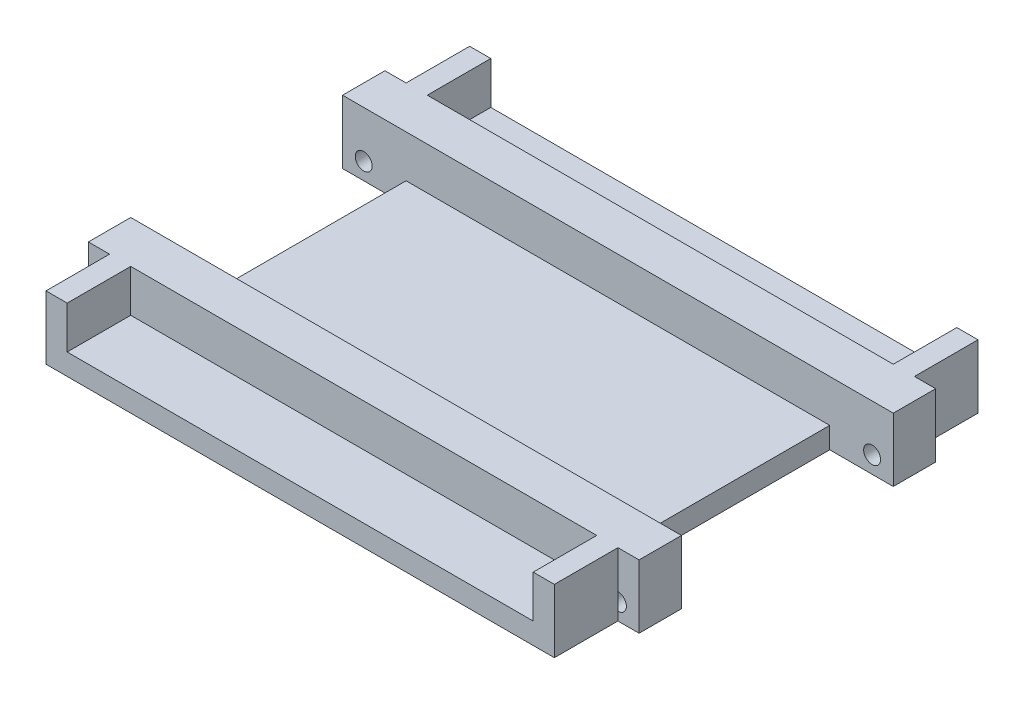
SolidWorks part; units mm, degrees
ref_plane "Front Plane" through (0, 0, 0) normal (0, 0, 1) x (1, 0, 0)
ref_plane "Top Plane" through (0, 0, 0) normal (0, 1, 0) x (1, 0, 0)
ref_plane "Right Plane" through (0, 0, 0) normal (1, 0, 0) x (0, 0, -1)
sketch "Sketch1" plane through (0, 0, 0) normal (0, 1, 0) x (1, 0, 0)
  line L1 (-50, 25) -> (50, 25)
  line L2 (-50, 25) -> (-50, -25)
  line L3 (-50, -25) -> (50, -25)
  line L4 (50, 25) -> (50, -25)
  line L5 (-50, 25) -> (50, -25) construction
  line L6 (-50, -25) -> (50, 25) construction
  point P0 (0, 0)
  dimension "D1" = 100
  dimension "D2" = 50
extrude "Boss-Extrude1" add sketch "Sketch1" along normal blind 5
sketch "Sketch2" plane through (0, 0, 25) normal (0, 0, 1) x (1, 0, 0)
  line L1 (-65, 15) -> (65, 15)
  line L2 (-65, 15) -> (-65, 0)
  line L3 (-65, 0) -> (65, 0)
  line L4 (65, 15) -> (65, 0)
  line L5 (-65, 15) -> (65, 0) construction
  line L6 (-65, 0) -> (65, 15) construction
  line L7 (-50, 5) -> (50, 5) construction
  point P0 (0, 7.5)
  dimension "D1" = 130
  dimension "D2" = 15
  dimension "D3" = 10
extrude "Boss-Extrude2" add sketch "Sketch2" along normal blind 10
sketch "Sketch3" plane through (0, 0, -25) normal (0, 0, -1) x (-1, 0, 0)
  line L1 (-65, 15) -> (65, 15)
  line L2 (-65, 15) -> (-65, 0)
  line L3 (-65, 0) -> (65, 0)
  line L4 (65, 15) -> (65, 0)
extrude "Boss-Extrude3" add sketch "Sketch3" along normal blind 10
sketch "Sketch4" plane through (0, 0, 35) normal (0, 0, 1) x (1, 0, 0)
  line L0 (-65, 15) -> (-65, 0) construction
  line L1 (-65, 0) -> (65, 0) construction
  circle A0 centre (-60, 4) radius 2
  dimension "D1" = 4
  dimension "D2" = 5
  dimension "D3" = 4
extrude "Cut-Extrude1" cut sketch "Sketch4" against normal through all
sketch "Sketch5" plane through (0, 0, 35) normal (0, 0, 1) x (1, 0, 0)
  line L0 (65, 0) -> (65, 15) construction
  line L1 (-65, 0) -> (65, 0) construction
  circle A0 centre (60, 4) radius 2
  dimension "D1" = 4
  dimension "D2" = 5
  dimension "D3" = 4
extrude "Cut-Extrude2" cut sketch "Sketch5" against normal through all
sketch "Sketch7" plane through (0, 0, 35) normal (0, 0, 1) x (1, 0, 0)
  line L0 (-65, 0) -> (65, 0) construction
  line L1 (-60, 0) -> (60, 0)
  line L2 (-60, 0) -> (-60, 5)
  line L3 (-60, 5) -> (60, 5)
  line L4 (60, 0) -> (60, 5)
  line L5 (-65, 15) -> (-65, 0) construction
  dimension "D1" = 120
  dimension "D2" = 5
  dimension "D3" = 5
extrude "Boss-Extrude4" add sketch "Sketch7" along normal blind 15
sketch "Sketch8" plane through (0, 5, 0) normal (0, 1, 0) x (1, 0, 0)
  line L0 (65, -35) -> (-65, -35) construction
  line L1 (-60, -50) -> (-55, -50)
  line L2 (-60, -50) -> (-60, -35)
  line L3 (-60, -35) -> (-55, -35)
  line L4 (-55, -50) -> (-55, -35)
  line L6 (60, -50) -> (55, -50)
  line L7 (60, -50) -> (60, -35)
  line L8 (60, -35) -> (55, -35)
  line L9 (55, -50) -> (55, -35)
  dimension "D1" = 5
  dimension "D2" = 110
extrude "Boss-Extrude5" add sketch "Sketch8" along normal blind 10
sketch "Sketch11" plane through (0, 0, -35) normal (0, 0, -1) x (-1, 0, 0)
  line L0 (60, 6) -> (60, 2) construction
  line L1 (-60, 0) -> (60, 0)
  line L2 (-60, 0) -> (-60, 5)
  line L3 (-60, 5) -> (60, 5)
  line L4 (60, 0) -> (60, 5)
  dimension "D1" = 5
extrude "Boss-Extrude6" add sketch "Sketch11" along normal blind 15
sketch "Sketch12" plane through (0, 5, 0) normal (0, 1, 0) x (1, 0, 0)
  line L0 (-65, 35) -> (65, 35) construction
  line L1 (-60, 50) -> (-55, 50)
  line L2 (-60, 50) -> (-60, 35)
  line L3 (-60, 35) -> (-55, 35)
  line L4 (-55, 50) -> (-55, 35)
  line L6 (60, 50) -> (55, 50)
  line L7 (60, 50) -> (60, 35)
  line L8 (60, 35) -> (55, 35)
  line L9 (55, 50) -> (55, 35)
  dimension "D1" = 110
  dimension "5" = 5
extrude "Boss-Extrude7" add sketch "Sketch12" along normal blind 10
